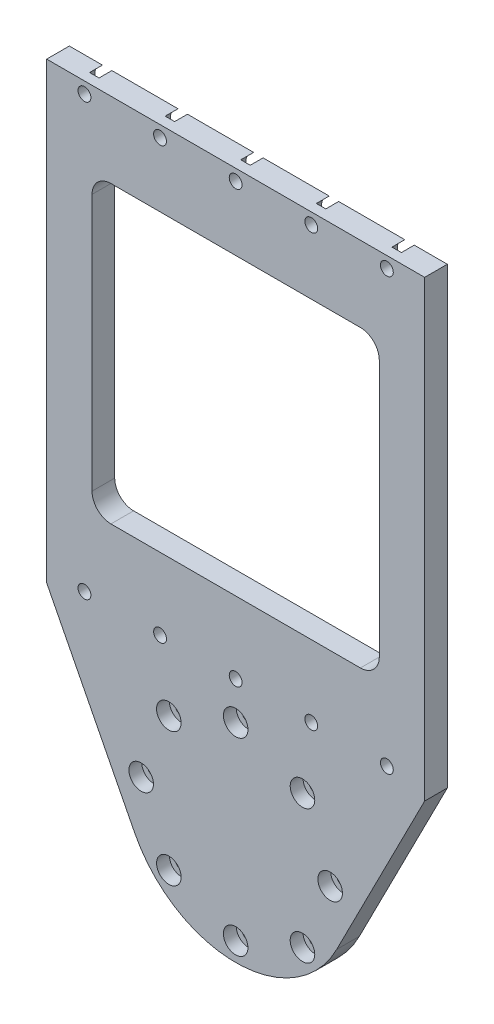
SolidWorks part; units mm, degrees
material "6061-T6 (SS)"
ref_plane "Front Plane" through (0, 0, 0) normal (0, 0, 1) x (1, 0, 0)
ref_plane "Top Plane" through (0, 0, 0) normal (0, 1, 0) x (1, 0, 0)
ref_plane "Right Plane" through (0, 0, 0) normal (1, 0, 0) x (0, 0, -1)
sketch "Sketch1" plane through (0, 0, 0) normal (0, 0, 1) x (1, 0, 0)
  line L0 (-30, 0) -> (-30, 152)
  line L1 (-30, 152) -> (30, 152)
  line L2 (30, 152) -> (30, 0)
  arc A0 (-30, 0) -> (30, 0) centre (0, 0) ccw
  dimension "D1" = 60
  dimension "D2" = 152
extrude "Boss-Extrude1" add sketch "Sketch1" along normal blind 6
sketch "Sketch7" plane through (0, 0, 6) normal (0, 0, 1) x (1, 0, 0)
  line L0 (-50, 32) -> (-26.7242, -13.6315)
  line L1 (30, 152) -> (50, 152)
  line L2 (30, 152) -> (30, 32)
  line L3 (30, 32) -> (50, 32) construction
  line L4 (50, 152) -> (50, 32)
  line L5 (-30, 152) -> (-50, 152)
  line L6 (-30, 152) -> (-30, 32)
  line L7 (-30, 32) -> (-50, 32) construction
  line L8 (-50, 152) -> (-50, 32)
  line L10 (26.7242, -13.6315) -> (50, 32)
  line L13 (30, 0) -> (30, 152)
  line L14 (30, 152) -> (-30, 152)
  line L15 (-30, 152) -> (-30, 0)
  line L16 (30, 0) -> (30, 152)
  line L17 (30, 152) -> (-30, 152)
  line L18 (-30, 152) -> (-30, 0)
  arc A1 (-30, 0) -> (30, 0) centre (0, 0) ccw
  arc A2 (-30, 0) -> (30, 0) centre (0, 0) ccw
  arc M9 (-30, 0) -> (30, 0) centre (0, 0) ccw
  line M10 (30, 0) -> (30, 152)
  line M12 (-30, 152) -> (-30, 0)
  dimension "D1" = 100
  dimension "D2" = 32
  dimension "D3" = 0
  dimension "D4" = 20
extrude "Boss-Extrude2" add sketch "Sketch7" against normal up to surface (6 mm away) contours L5 L8 L0 M9 M12 | L10 L4 L1 M9 M10 up to face at (0, 68.5, 0)
sketch "Sketch2" plane through (0, 0, 6) normal (0, 0, 1) x (1, 0, 0)
  circle A0 centre (0, 0) radius 25
  point P6 (0, 25)
  point P12 (17.6777, 17.6777)
  point P13 (25, 0)
  point P14 (17.6777, -17.6777)
  point P15 (0, -25)
  point P16 (-17.6777, -17.6777)
  point P17 (-25, 0)
  point P18 (-17.6777, 17.6777)
  dimension "D1" = 50
  dimension "D2" = 8
hole_wizard "CBORE for M3 Hex Socket Head Cap Screw1" positions "Sketch2" profile "Sketch3" counterbore size "M3" standard "DIN" end condition through all
sketch "Sketch3" plane through (-17.6777, 17.6777, 6) normal (1, 0, 0) x (0, -1, 0)
  line L0 (0, 0) -> (0, 6)
  line L1 (0, 6) -> (1.7, 6)
  line L3 (1.7, 6) -> (1.7, 3.4)
  line L4 (1.7, 3.4) -> (3.25, 3.4)
  line L5 (3.25, 3.4) -> (3.25, 0)
  line L7 (3.25, 0) -> (0, 0)
  line L11 (0, -6.35) -> (0, 107.95) construction
  dimension "Thru Hole Dia." = 3.4
  dimension "Thru Hole Depth" = 6
  dimension "C'Bore Dia." = 6.5
  dimension "C'Bore Depth" = 3.4
sketch "Sketch4" plane through (0, 0, 0) normal (0, 0, -1) x (-1, 0, 0)
  line L0 (-50, 35) -> (50, 35) construction
  line L3 (-50, 152) -> (50, 152) construction
  line L4 (0, 152) -> (0, 149) construction
  line L8 (50, 32) -> (50, 152) construction
  line L9 (-50, 32) -> (-50, 152) construction
  point P7 (0, 35)
  point P23 (20, 35)
  point P24 (40, 35)
  point P25 (0, 35)
  point P26 (20, 35)
  point P27 (-20, 35)
  point P28 (0, 35)
  point P29 (-20, 35)
  point P30 (-40, 35)
  point P46 (0, 149)
  point P59 (20, 149)
  point P60 (40, 149)
  point P61 (0, 149)
  point P62 (20, 149)
  point P63 (-20, 149)
  point P64 (0, 149)
  point P65 (-20, 149)
  point P66 (-40, 149)
  point P72 (0, 0)
  point P79 (-64.1339, 35)
  point P80 (0, 0)
  point P83 (0, 0)
  dimension "D1" = 35
  dimension "D5" = 3
  dimension "D4" = 3
  dimension "D6" = 3
  dimension "D3" = 3
  dimension "D2" = 3
hole_wizard "CBORE for M3 Hex Socket Head Cap Screw2" positions "Sketch4" profile "Sketch6" counterbore size "M3" standard "DIN"
sketch "Sketch6" plane through (40, 149, 0) normal (1, 0, 0) x (0, 1, 0)
  line L0 (0, 0) -> (0, 11.0215)
  line L1 (0, 11.0215) -> (1.7, 10)
  line L2 (1.7, 10) -> (1.7, 3.4)
  line L3 (1.7, 3.4) -> (3.25, 3.4)
  line L4 (3.25, 3.4) -> (3.25, 0)
  line L5 (3.25, 0) -> (0, 0)
  line L10 (0, 11.0215) -> (-1.7, 10) construction
  line L11 (0, -6.35) -> (0, 107.95) construction
  dimension "Hole Dia." = 3.4
  dimension "Hole Depth" = 10
  dimension "C'Bore Dia." = 6.5
  dimension "C'Bore Depth" = 3.4
  dimension "Drill Angle" = 118
sketch "Sketch8" plane through (0, 0, 0) normal (0, 0, -1) x (-1, 0, 0)
  line L0 (50, 32) -> (50, 152) construction
  line L1 (-38, 132) -> (38, 132)
  line L2 (-38, 132) -> (-38, 54)
  line L3 (-38, 54) -> (38, 54)
  line L4 (38, 132) -> (38, 54)
  line L5 (-50, 152) -> (-50, 32) construction
  line L6 (-38.75, 152) -> (-21.25, 152) construction
  dimension "D1" = 12
  dimension "D2" = 12
  dimension "D3" = 20
  dimension "D4" = 78
extrude "Cut-Extrude1" cut sketch "Sketch8" against normal up to next and the other way through all
fillet "Fillet2" radius 5 4 edges at (-38, 54, 3) (38, 54, 3) (38, 132, 3) (-38, 132, 3)
